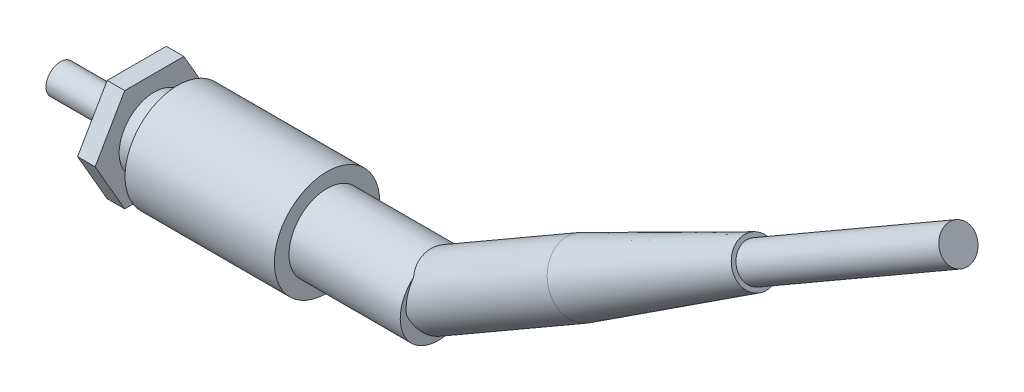
SolidWorks part; units mm, degrees
ref_plane "Front Plane" through (0, 0, 0) normal (0, 0, 1) x (1, 0, 0)
ref_plane "Top Plane" through (0, 0, 0) normal (0, 1, 0) x (1, 0, 0)
ref_plane "Right Plane" through (0, 0, 0) normal (1, 0, 0) x (0, 0, -1)
sketch "Sketch1" plane through (0, 0, 0) normal (0, 0, 1) x (1, 0, 0)
  line L0 (-50, 0) -> (0, 0)
  line L1 (0, 0) -> (90.9327, 52.5)
  dimension "D1" = 50
  dimension "D2" = 105
  dimension "D3" = 150
ref_plane "Plane1" through (-50, 0, 0) normal (1, 0, 0) x (0, 0, -1)
sketch "Sketch2" plane through (-50, 0, 0) normal (1, 0, 0) x (0, 0, -1)
  line L1 (-5.0518, 8.75) -> (-10.1036, 0)
  line L2 (-10.1036, 0) -> (-5.0518, -8.75)
  line L3 (-5.0518, -8.75) -> (5.0518, -8.75)
  line L4 (5.0518, -8.75) -> (10.1036, 0)
  line L5 (10.1036, 0) -> (5.0518, 8.75)
  line L6 (5.0518, 8.75) -> (-5.0518, 8.75)
  circle A0 centre (0, 0) radius 8.75 construction
  dimension "D1" = 17.5
extrude "Boss-Extrude1" add sketch "Sketch2" along normal blind 3
sketch "Sketch3" plane through (-47, 0, 0) normal (1, 0, 0) x (0, 0, -1)
  circle A0 centre (0, 0) radius 6
  dimension "D1" = 12
extrude "Boss-Extrude2" add sketch "Sketch3" along normal blind 4
sketch "Sketch4" plane through (-43, 0, 0) normal (1, 0, 0) x (0, 0, -1)
  circle A0 centre (0, 0) radius 9
  dimension "D1" = 18
extrude "Boss-Extrude3" add sketch "Sketch4" along normal blind 25.5
sketch "Sketch5" plane through (-17.5, 0, 0) normal (1, 0, 0) x (0, 0, -1)
  circle A0 centre (0, 0) radius 6.5
  dimension "D1" = 13
extrude "Boss-Extrude4" add sketch "Sketch5" along normal blind 19
sketch "Sketch6" plane through (-50, 0, 0) normal (-1, 0, 0) x (0, 0, 1)
  circle A0 centre (0, 0) radius 2.5
  dimension "D1" = 5
extrude "Boss-Extrude5" add sketch "Sketch6" along normal blind 13
sketch "Sketch7" plane through (1.5, 0, 0) normal (1, 0, 0) x (0, 0, -1)
  line L0 (-1000, 0) -> (49000, 0) construction
ref_plane "Plane2" through (1.125, 0.6495, 0) normal (0.866, 0.5, 0) x (0, 0, -1)
sketch "Sketch8" plane through (1.125, 0.6495, 0) normal (0.866, 0.5, 0) x (0, 0, -1)
  circle A0 centre (0, 0) radius 5.5
  dimension "D1" = 11
extrude "Boss-Extrude6" add sketch "Sketch8" along normal blind 29
sketch "Sketch9" plane through (26.2397, 15.1495, 0) normal (0.866, 0.5, 0) x (0, 0, -1)
  circle A0 centre (0, 0) radius 5.5
extrude "Boss-Extrude7" add sketch "Sketch9" along normal blind 34 draft 3
sketch "Sketch10" plane through (55.6846, 32.1495, 0) normal (0.866, 0.5, 0) x (0, 0, -1)
  circle A0 centre (0, 0) radius 3
  dimension "D1" = 6
extrude "Boss-Extrude8" add sketch "Sketch10" along normal blind 40
